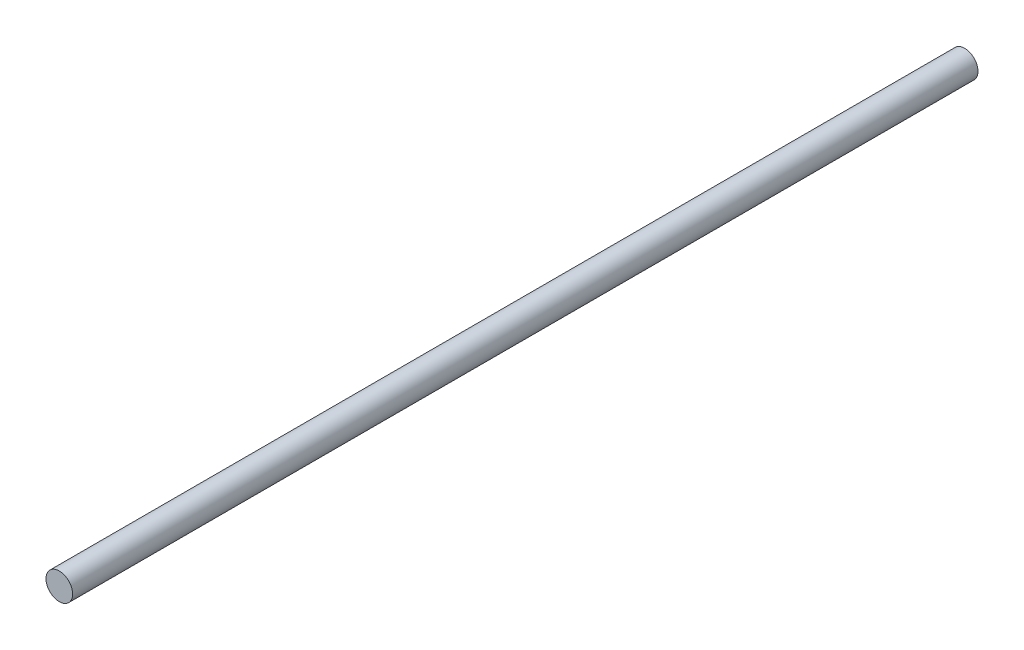
SolidWorks part; units mm, degrees
ref_plane "Front Plane" through (0, 0, 0) normal (0, 0, 1) x (1, 0, 0)
ref_plane "Top Plane" through (0, 0, 0) normal (0, 1, 0) x (1, 0, 0)
ref_plane "Right Plane" through (0, 0, 0) normal (1, 0, 0) x (0, 0, -1)
sketch "Sketch1" plane through (0, 0, 0) normal (0, 0, 1) x (1, 0, 0)
  circle A0 centre (0, 0) radius 3.175
  dimension "D1" = 6.35
extrude "Boss-Extrude1" add sketch "Sketch1" along normal blind 215.9
